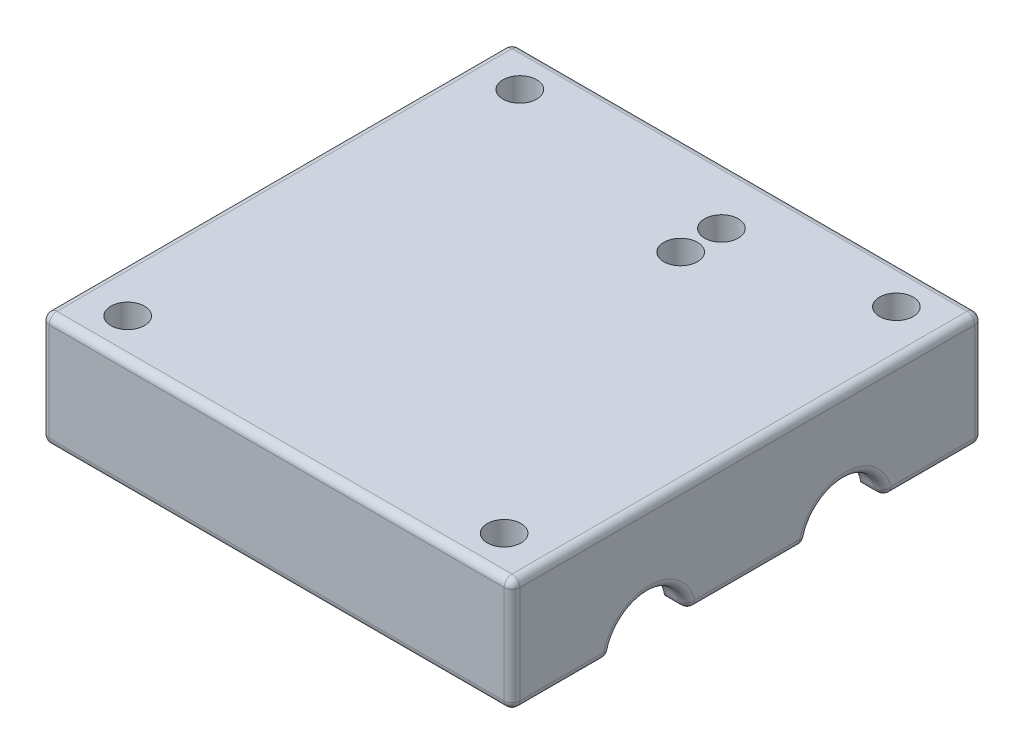
SolidWorks part; units mm, degrees
ref_plane "Front Plane" through (0, 0, 0) normal (0, 0, 1) x (1, 0, 0)
ref_plane "Top Plane" through (0, 0, 0) normal (0, 1, 0) x (1, 0, 0)
ref_plane "Right Plane" through (0, 0, 0) normal (1, 0, 0) x (0, 0, -1)
sketch "Sketch1" plane through (0, 0, 0) normal (0, 1, 0) x (1, 0, 0)
  line L1 (-30, -30) -> (30, -30)
  line L2 (-30, -30) -> (-30, 30)
  line L3 (-30, 30) -> (30, 30)
  line L4 (30, -30) -> (30, 30)
  line L5 (-30, -30) -> (30, 30) construction
  line L6 (-30, 30) -> (30, -30) construction
  point P0 (0, 0)
  dimension "D1" = 60
  dimension "D2" = 60
extrude "Boss-Extrude1" add sketch "Sketch1" along normal blind 30
sketch "Sketch2" plane through (30, 0, 0) normal (1, 0, 0) x (0, 0, -1)
  line L0 (0, 0) -> (0, 30) construction
  line L1 (-30, 30) -> (30, 30) construction
  line L2 (-30, 15) -> (-12.5, 15) construction
  line L3 (-30, 30) -> (-30, 0) construction
  line L4 (-12.5, 15) -> (12.5, 15) construction
  line L5 (12.5, 15) -> (30, 15) construction
  line L6 (30, 30) -> (30, 0) construction
  circle A0 centre (-12.5, 15) radius 7.5
  circle A1 centre (12.5, 15) radius 7.5
  point P15 (0, 15)
  dimension "D2" = 15
  dimension "D1" = 25
extrude "Cut-Extrude1" cut sketch "Sketch2" against normal up to next
sketch "Sketch6" plane through (0, 0, 0) normal (1, 0, 0) x (0, 0, -1)
  circle A0 centre (12.5, 15) radius 7.5 construction
  circle A1 centre (-12.5, 15) radius 7.5 construction
  circle A2 centre (12.5, 15) radius 7.5
  circle A3 centre (-12.5, 15) radius 7.5
extrude "Boss-Extrude2" add sketch "Sketch6" along normal mid plane 3.6
sketch "Sketch3" plane through (0, 30, 0) normal (0, 1, 0) x (1, 0, 0)
  line L0 (0, 30) -> (0, 20) construction
  line L3 (-30, 30) -> (-30, -30) construction
  line L4 (-24, -25) -> (24, -25) construction
  line L5 (-24, -25) -> (-24, 25) construction
  line L6 (-24, 25) -> (24, 25) construction
  line L7 (24, -25) -> (24, 25) construction
  line L8 (-24, -25) -> (24, 25) construction
  line L9 (-24, 25) -> (24, -25) construction
  line L10 (30, 30) -> (-30, 30) construction
  line L11 (0, 20) -> (0, -20) construction
  line L12 (0, -20) -> (0, -30) construction
  line L13 (-30, -30) -> (30, -30) construction
  circle A2 centre (-24, 25) radius 2.15
  circle A3 centre (-24, -25) radius 2.15
  circle A4 centre (24, -25) radius 2.15
  circle A5 centre (24, 25) radius 2.15
  point P10 (0, 0)
  dimension "D1" = 10
  dimension "D4" = 50
  dimension "D5" = 6
extrude "Cut-Extrude2" cut sketch "Sketch3" against normal blind 5
sketch "Sketch7" plane through (30, 0, 0) normal (1, 0, 0) x (0, 0, -1)
  circle A0 centre (12.5, 15) radius 7.5 construction
  circle A1 centre (-12.5, 15) radius 7.5 construction
  circle A2 centre (12.5, 15) radius 7.5
  circle A3 centre (-12.5, 15) radius 7.5
  circle A4 centre (-12.5, 15) radius 5
  circle A5 centre (12.5, 15) radius 5
  dimension "D1" = 10
extrude "Boss-Extrude3" add sketch "Sketch7" against normal blind 3.6
mirror "Mirror1" about plane through (0, 0, 0) normal (1, 0, 0) of "Boss-Extrude3"
sketch "Sketch4" plane through (30, 0, 0) normal (1, 0, 0) x (0, 0, -1)
  line L0 (-30, 15) -> (30, 15) construction
  line L1 (-30, 30) -> (-30, 0) construction
  line L2 (30, 30) -> (30, 0) construction
  line L4 (-30, 14.5) -> (30, 14.5)
  line L5 (-30, 14.5) -> (-30, 15.5)
  line L6 (-30, 15.5) -> (30, 15.5)
  line L7 (30, 14.5) -> (30, 15.5)
  line L8 (-30, 14.5) -> (30, 15.5) construction
  line L9 (-30, 15.5) -> (30, 14.5) construction
  point P6 (0, 15)
  dimension "D1" = 1
extrude "Cut-Extrude3" cut sketch "Sketch4" against normal through all
sketch "Sketch5" plane through (0, 15.5, 0) normal (0, -1, 0) x (1, 0, 0)
  line L0 (-30, 24.9917) -> (-18, 24.9917) construction
  line L2 (-18, 24.9917) -> (18, 24.9917) construction
  line L3 (18, 24.9917) -> (30, 24.9917) construction
  line L5 (30, 0) -> (18, 0) construction
  line L7 (18, 0) -> (-18, 0) construction
  line L8 (-18, 0) -> (-30, 0) construction
  line L10 (-30, -24.9917) -> (-18, -24.9917) construction
  line L12 (-18, -24.9917) -> (18, -24.9917) construction
  line L13 (18, -24.9917) -> (30, -24.9917) construction
  line L15 (-30, -7.5251) -> (-30, 7.5251) construction
  line L16 (30, -7.5251) -> (30, 7.5251) construction
  line L17 (14.1, -19.9833) -> (14.1, -30) construction
  line L18 (1.8, -19.9833) -> (26.4, -19.9833) construction
  line L19 (-30, -30) -> (30, -30) construction
  line L20 (30, -30) -> (30, -17.4749) construction
  line L21 (-30, -30) -> (-30, -17.4749) construction
  line L22 (-14.1, 19.9833) -> (-14.1, 30) construction
  line L23 (-1.8, 19.9833) -> (-26.4, 19.9833) construction
  line L24 (-30, 30) -> (30, 30) construction
  line L25 (-30, 17.4749) -> (-30, 30) construction
  line L26 (30, 17.4749) -> (30, 30) construction
  circle A0 centre (18, 24.9917) radius 2.15
  circle A1 centre (-18, 24.9917) radius 2.15
  circle A2 centre (-18, 0) radius 2.15
  circle A3 centre (18, 0) radius 2.15
  circle A4 centre (18, -24.9917) radius 2.15
  circle A5 centre (-18, -24.9917) radius 2.15
  point P10 (14.1, -24.9917)
  point P17 (-14.1, 24.9917)
  dimension "D2" = 4.3
  dimension "D1" = 12
extrude "Cut-Extrude4" cut sketch "Sketch5" against normal blind 8
fillet "Fillet2" radius 1 32 edges at (28.2, 15.5, 17.4749) (28.2, 15.5, 7.5251) (26.4, 20, 12.5) (28.2, 15.5, -7.5251) (28.2, 15.5, -17.4749) (26.4, 20, -12.5) (-28.2, 15.5, 17.4749) (-28.2, 15.5, 7.5251) (-26.4, 20, 12.5) (-28.2, 15.5, -7.5251) (-28.2, 15.5, -17.4749) (-26.4, 20, -12.5) (-30, 30, 0) (-30, 15.5, 23.7375) (-30, 20, 12.5) (-30, 15.5, 0) (-30, 20, -12.5) (-30, 15.5, -23.7375) (0, 30, -30) (-30, 22.75, -30) (0, 15.5, -30) (30, 30, 0) (30, 22.75, -30) (30, 15.5, -23.7375) (30, 20, -12.5) (30, 15.5, 0) (30, 20, 12.5) (30, 15.5, 23.7375) (0, 30, 30) (30, 22.75, 30) (0, 15.5, 30) (-30, 22.75, 30)
sketch "Sketch8" [suppressed] plane through (0, 30, 0) normal (0, 1, 0) x (1, 0, 0)
  line L0 (-18.9, 30) -> (-18.9, -30) construction
  line L5 (-29, 30) -> (29, 30) construction
  line L7 (29, -30) -> (-29, -30) construction
  line L8 (18.9, 30) -> (18.9, -30) construction
  line L9 (-30, -29) -> (-30, 29) construction
  line L10 (30, 29) -> (30, -29) construction
  circle A0 centre (0, 20) radius 2.15
  circle A1 centre (0, -20) radius 2.15
  point P6 (0, 0)
  point P14 (0, -20)
  point P15 (0, 20)
  point P16 (-18.9, 0)
  point P17 (18.9, 0)
  dimension "D1" = 11.1
  dimension "D2" = 11.1
sketch "Sketch10" plane through (30, 0, 0) normal (1, 0, 0) x (0, 0, -1)
  circle A1 centre (-12.5, 15) radius 5
  circle A3 centre (12.5, 15) radius 5
  circle A4 centre (-12.5, 15) radius 4 construction
  circle A5 centre (12.5, 15) radius 4 construction
  dimension "D1" = 10
extrude "Cut-Extrude5" cut sketch "Sketch10" against normal through all
sketch "Sketch11" plane through (0, 30, 0) normal (0, 1, 0) x (1, 0, 0)
  line L0 (4.2, 30) -> (4.2, -29) construction
  line L1 (-29, 30) -> (29, 30) construction
  line L2 (-29, -29) -> (29, -29) construction
  line L3 (-30, -29) -> (-30, 29) construction
  circle A0 centre (4.2, 22.5) radius 2.15
  circle A1 centre (4.2, 17.3) radius 2.15
  dimension "D2" = 4.3
  dimension "D3" = 4.3
  dimension "D1" = 34.2
  dimension "D4" = 7.5
  dimension "D5" = 12.7
extrude "L-Arm Holes" cut sketch "Sketch11" against normal blind 5
sketch "Sketch15" plane through (0, 30, 0) normal (0, 1, 0) x (1, 0, 0)
  line L0 (0, 29) -> (0, -30) construction
  line L1 (29, 29) -> (-29, 29) construction
  line L2 (29, -30) -> (-29, -30) construction
  line L3 (-29, 30) -> (29, 30) construction
  circle A0 centre (0, 20) radius 2.15
  circle A1 centre (0, -20) radius 2.15
  dimension "D1" = 4.3
  dimension "D3" = 10
  dimension "D2" = 10
extrude "R&P Holes" [suppressed] cut sketch "Sketch15" against normal blind 5
sketch "Sketch12" plane through (0, 30, 0) normal (0, 1, 0) x (1, 0, 0)
  line L0 (-29, -29) -> (29, -29) construction
  line L4 (-29, 29) -> (-17, 29)
  line L5 (-29, 29) -> (-29, -29)
  line L6 (-29, -29) -> (-17, -29)
  line L7 (-17, 29) -> (-17, -29)
  dimension "D1" = 12
sketch "Sketch13" plane through (0, 30, 0) normal (0, 1, 0) x (1, 0, 0)
  line L0 (-17, 39.9427) -> (-17, -37.6325) construction
  line L1 (-29, 29) -> (-29, -29) construction
  dimension "D1" = 12
ref_plane "Plane1" through (-17, 0, 0) normal (1, 0, 0) x (0, 0, -1)
sketch "Sketch14" plane through (0, 30, 0) normal (0, 1, 0) x (1, 0, 0)
  circle A0 centre (0, 0) radius 9
  point P0 (0, 0)
  dimension "D1" = 18
